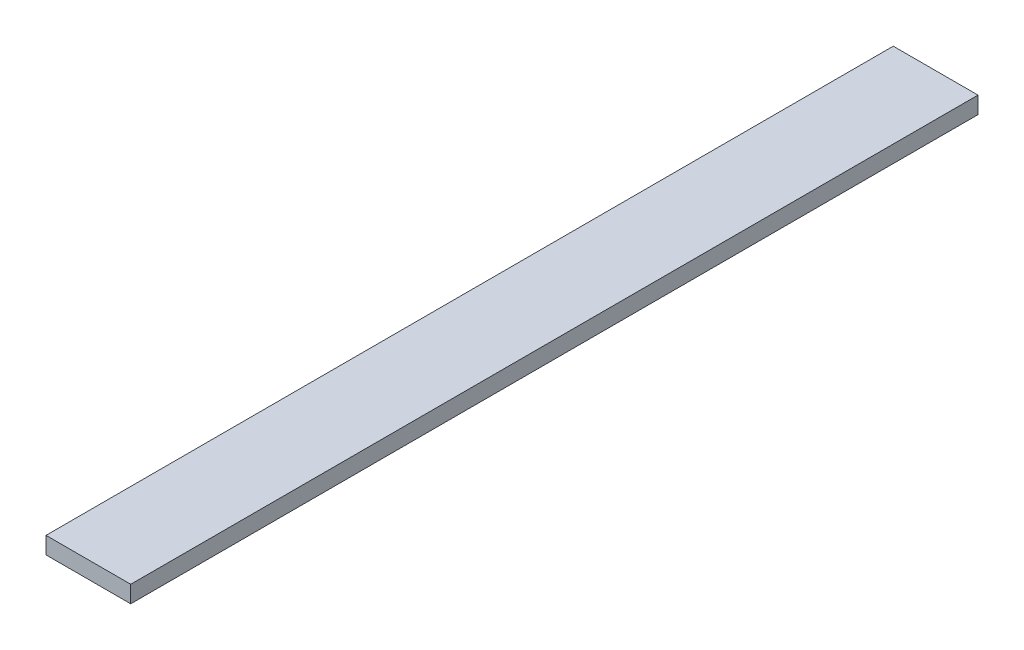
SolidWorks part; units mm, degrees
ref_plane "Front Plane" through (0, 0, 0) normal (0, 0, 1) x (1, 0, 0)
ref_plane "Top Plane" through (0, 0, 0) normal (0, 1, 0) x (1, 0, 0)
ref_plane "Right Plane" through (0, 0, 0) normal (1, 0, 0) x (0, 0, -1)
sketch "Sketch1" plane through (0, 0, 0) normal (0, 1, 0) x (1, 0, 0)
  line L1 (0, 0) -> (25, 0)
  line L2 (0, 0) -> (0, 250)
  line L3 (0, 250) -> (25, 250)
  line L4 (25, 0) -> (25, 250)
  dimension "D1" = 25
  dimension "D2" = 250
extrude "Boss-Extrude1" add sketch "Sketch1" along normal blind 5
